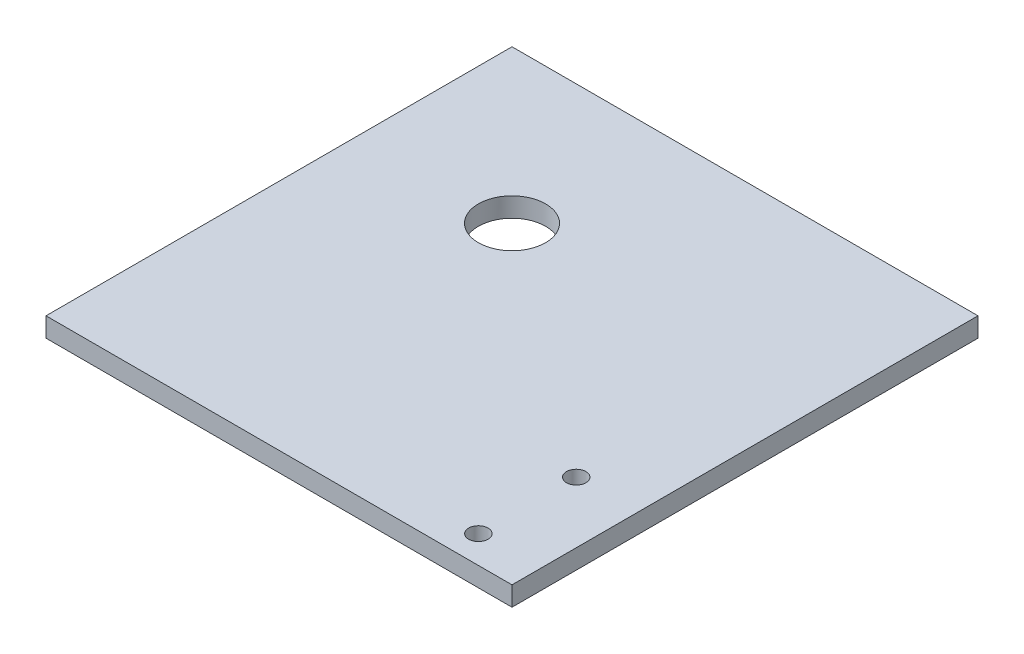
SolidWorks part; units mm, degrees
ref_plane "Front Plane" through (0, 0, 0) normal (0, 0, 1) x (1, 0, 0)
ref_plane "Top Plane" through (0, 0, 0) normal (0, 1, 0) x (1, 0, 0)
ref_plane "Right Plane" through (0, 0, 0) normal (1, 0, 0) x (0, 0, -1)
sketch "Sketch1" plane through (0, 0, 0) normal (0, 0, 1) x (1, 0, 0)
  line L0 (0, 3.175) -> (0, -3.175)
  line L1 (-76.2, 0) -> (76.2, 0) construction
  point P6 (0, 0)
  dimension "Width" = 152.4
  dimension "Thickness" = 6.35
sketch "Sketch2" plane through (0, 0, 0) normal (1, 0, 0) x (0, 0, -1)
  line L0 (76.2, 0) -> (-76.2, 0) construction
  point P4 (0, 0)
  dimension "Length" = 152.4
sketch "Sketch3" plane through (0, 0, 0) normal (0, 1, 0) x (1, 0, 0)
  line L5 (-76.2, -76.2) -> (76.2, -76.2)
  line L6 (-76.2, -76.2) -> (-76.2, 76.2)
  line L7 (-76.2, 76.2) -> (76.2, 76.2)
  line L8 (76.2, -76.2) -> (76.2, 76.2)
  line L9 (-76.2, -76.2) -> (76.2, 76.2) construction
  line L10 (-76.2, 76.2) -> (76.2, -76.2) construction
  point P0 (0, 0)
  point P1 (0, 0)
  dimension "D1" = 152.4
  dimension "D2" = 152.4
extrude "Boss-Extrude1" add sketch "Sketch3" along normal mid plane 6.35
sketch "Sketch4" plane through (0, 3.175, 0) normal (0, 1, 0) x (1, 0, 0)
  line L0 (76.2, 76.2) -> (-76.2, 76.2) construction
  line L1 (-76.2, 76.2) -> (-76.2, -76.2) construction
  circle A0 centre (-26.2, 26.2) radius 11
  point P2 (0, 0)
  dimension "D1" = 50
  dimension "D2" = 50
extrude "Cut-Extrude1" cut sketch "Sketch4" against normal blind 10
sketch "Sketch5" plane through (0, 3.175, 0) normal (0, 1, 0) x (1, 0, 0)
  line L0 (56.2, -26.2) -> (56.2, -76.2) construction
  line L1 (76.2, -76.2) -> (36.2, -76.2)
  line L2 (76.2, -76.2) -> (76.2, -26.2)
  line L5 (36.2, -51.2) -> (76.2, -51.2) construction
  circle A0 centre (56.2, -35.2) radius 3.175
  circle A1 centre (56.2, -67.2) radius 3.175
  dimension "D1" = 6.35
  dimension "D2" = 32
extrude "Cut-Extrude5" cut sketch "Sketch5" against normal blind 10 contours A0 | A1
equation "\"D1@Sketch3\"=\"Width@Sketch1\""
equation "\"D2@Sketch3\"=\"Length@Sketch2\""
equation "\"D1@Boss-Extrude1\" = \"Thickness@Sketch1\""
